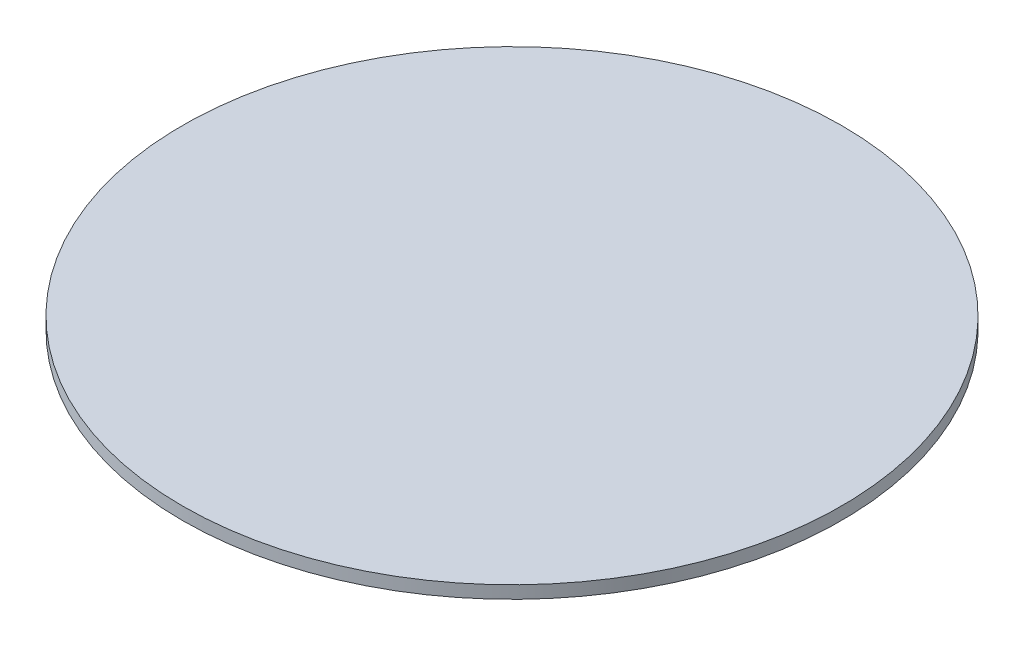
SolidWorks part; units mm, degrees
ref_plane "Front Plane" through (0, 0, 0) normal (0, 0, 1) x (1, 0, 0)
ref_plane "Top Plane" through (0, 0, 0) normal (0, 1, 0) x (1, 0, 0)
ref_plane "Right Plane" through (0, 0, 0) normal (1, 0, 0) x (0, 0, -1)
sketch "Sketch1" plane through (0, 0, 0) normal (0, 1, 0) x (1, 0, 0)
  circle A0 centre (0, 0) radius 78.35
  dimension "D1" = 156.7
extrude "Boss-Extrude1" add sketch "Sketch1" along normal blind 3
